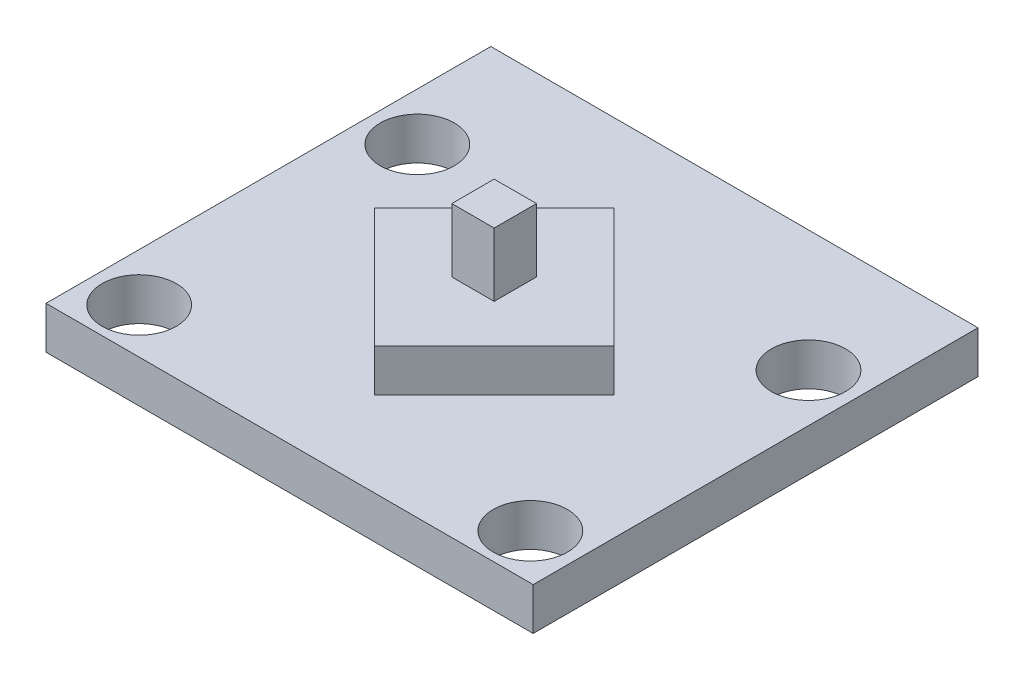
SolidWorks part; units mm, degrees
ref_plane "Front Plane" through (0, 0, 0) normal (0, 0, 1) x (1, 0, 0)
ref_plane "Top Plane" through (0, 0, 0) normal (0, 1, 0) x (1, 0, 0)
ref_plane "Right Plane" through (0, 0, 0) normal (1, 0, 0) x (0, 0, -1)
sketch "Sketch1" plane through (0, 0, 0) normal (0, 1, 0) x (1, 0, 0)
  line L1 (-11.5, -10.5) -> (11.5, -10.5)
  line L2 (-11.5, -10.5) -> (-11.5, 10.5)
  line L3 (-11.5, 10.5) -> (11.5, 10.5)
  line L4 (11.5, -10.5) -> (11.5, 10.5)
  line L5 (-11.5, -10.5) -> (11.5, 10.5) construction
  line L6 (-11.5, 10.5) -> (11.5, -10.5) construction
  point P0 (0, 0)
  dimension "D1" = 23
  dimension "D2" = 21
extrude "Boss-Extrude1" add sketch "Sketch1" along normal blind 2
sketch "Sketch2" plane through (0, 2, 0) normal (0, 1, 0) x (1, 0, 0)
  line L0 (0, 0) -> (0, 50000) construction
  line L1 (9.2333, 4.7641) -> (-9.2333, 4.7641) construction
  line L2 (9.2333, 4.7641) -> (9.2333, -8.3677) construction
  line L3 (9.2333, -8.3677) -> (-9.2333, -8.3677) construction
  line L4 (-9.2333, 4.7641) -> (-9.2333, -8.3677) construction
  line L5 (9.2333, 4.7641) -> (-9.2333, -8.3677) construction
  line L6 (9.2333, -8.3677) -> (-9.2333, 4.7641) construction
  line L7 (-11.5, -10.5) -> (11.5, -10.5) construction
  line L8 (-11.5, 10.5) -> (-11.5, -10.5) construction
  circle A0 centre (-9.2333, -8.3677) radius 1.75
  circle A1 centre (9.2333, -8.3677) radius 1.75
  circle A2 centre (9.2333, 4.7641) radius 1.75
  circle A3 centre (-9.2333, 4.7641) radius 1.75
  point P2 (0, -1.8018)
  point P10 (0, 0)
  point P14 (-9.2333, -8.3677)
  dimension "D1" = 3.5
  dimension "D2" = 2.1323
  dimension "D3" = 2.2667
extrude "Cut-Extrude1" cut sketch "Sketch2" against normal through all
sketch "Sketch3" plane through (0, 2, 0) normal (0, 1, 0) x (1, 0, 0)
  line L0 (0, 10.5) -> (0, -49989.5) construction
  line L1 (11.5, 10.5) -> (-11.5, 10.5) construction
  line L2 (-11.5, -10.5) -> (11.5, -10.5) construction
  line L3 (-5.6569, -0.8431) -> (0, -6.5)
  line L4 (-5.6569, -0.8431) -> (0, 4.8137)
  line L5 (0, 4.8137) -> (5.6569, -0.8431)
  line L6 (0, -6.5) -> (5.6569, -0.8431)
  line L7 (-5.6569, -0.8431) -> (5.6569, -0.8431) construction
  line L8 (0, 4.8137) -> (0, -6.5) construction
  point P4 (0, 10.5)
  point P5 (0, -0.8431)
  point P10 (0, 0)
  point P11 (0, -4.6744)
  dimension "D1" = 8
  dimension "D2" = 4
extrude "Boss-Extrude2" add sketch "Sketch3" along normal blind 2
sketch "Sketch4" plane through (0, 4, 0) normal (0, 1, 0) x (1, 0, 0)
  line L0 (-5.6569, -0.8431) -> (49994.3431, -0.8431) construction
  line L1 (0, 4.8137) -> (0, -49995.1863) construction
  line L3 (-1, -1.8431) -> (1, -1.8431)
  line L4 (-1, -1.8431) -> (-1, 0.1569)
  line L5 (-1, 0.1569) -> (1, 0.1569)
  line L6 (1, -1.8431) -> (1, 0.1569)
  line L7 (-1, -1.8431) -> (1, 0.1569) construction
  line L8 (-1, 0.1569) -> (1, -1.8431) construction
  point P8 (0, -0.8431)
  dimension "D1" = 2
extrude "Boss-Extrude3" add sketch "Sketch4" along normal blind 3
ref_plane "Plane1" through (0, 0, 0.8431) normal (0, 0, 1) x (1, 0, 0)
